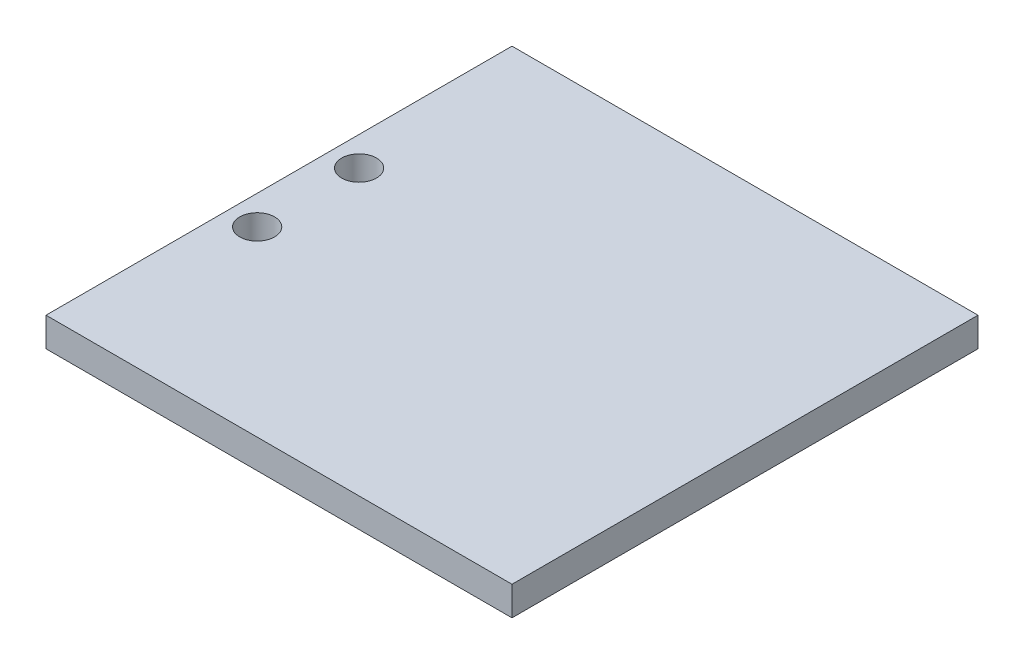
SolidWorks part; units mm, degrees
material "ABS PC"
ref_plane "Front Plane" through (0, 0, 0) normal (0, 0, 1) x (1, 0, 0)
ref_plane "Top Plane" through (0, 0, 0) normal (0, 1, 0) x (1, 0, 0)
ref_plane "Right Plane" through (0, 0, 0) normal (1, 0, 0) x (0, 0, -1)
sketch "Sketch1" plane through (0, 0, 0) normal (0, 1, 0) x (1, 0, 0)
  line L1 (-25.4, 25.4) -> (25.4, 25.4)
  line L2 (-25.4, 25.4) -> (-25.4, -25.4)
  line L3 (-25.4, -25.4) -> (25.4, -25.4)
  line L4 (25.4, 25.4) -> (25.4, -25.4)
  line L5 (-25.4, 25.4) -> (25.4, -25.4) construction
  line L6 (-25.4, -25.4) -> (25.4, 25.4) construction
  point P0 (0, 0)
  dimension "D1" = 50.8
  dimension "D2" = 50.8
extrude "Boss-Extrude1" add sketch "Sketch1" along normal blind 3.175
hole_wizard "#6 Clearance Hole1" positions "Sketch2" profile "Sketch3" hole size "#6" standard "ANSI Inch"
sketch "Sketch2" plane through (0, 3.175, 0) normal (0, 1, 0) x (1, 0, 0)
  line L0 (-25.4, 25.4) -> (-25.4, -25.4) construction
  point P0 (-22.225, 5.5562)
  point P2 (-22.225, -5.5562)
  dimension "D1" = 11.1125
  dimension "D2" = 5.5562
  dimension "D3" = 3.175
sketch "Sketch3" plane through (-22.225, 3.175, -5.5562) normal (1, 0, 0) x (0, 0, 1)
  line L0 (0, 0) -> (0, 13.8408)
  line L1 (0, 13.8408) -> (1.8986, 12.7)
  line L2 (1.8986, 12.7) -> (1.8986, 0)
  line L5 (1.8986, 0) -> (0, 0)
  line L10 (0, 13.8408) -> (-1.8986, 12.7) construction
  line L11 (0, -6.35) -> (0, 107.95) construction
  dimension "Hole Dia." = 3.7973
  dimension "Hole Depth" = 12.7
  dimension "Drill Angle" = 118
